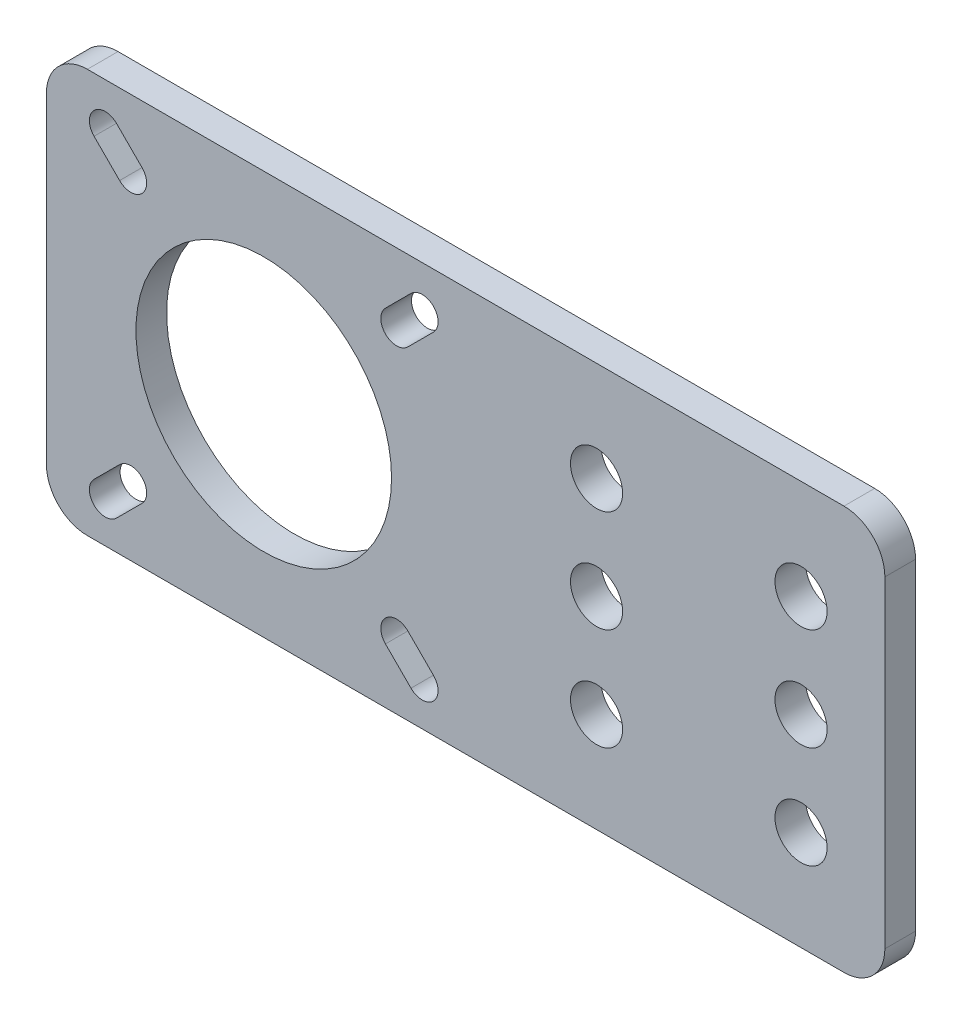
SolidWorks part; units mm, degrees
ref_plane "Alzado" through (0, 0, 0) normal (0, 0, 1) x (1, 0, 0)
ref_plane "Planta" through (0, 0, 0) normal (0, 1, 0) x (1, 0, 0)
ref_plane "Vista lateral" through (0, 0, 0) normal (1, 0, 0) x (0, 0, -1)
sketch "Croquis1" plane through (0, 0, 0) normal (0, 0, 1) x (1, 0, 0)
  line L1 (-36.0737, 51.8328) -> (37.9263, 51.8328)
  line L2 (-40.0737, 47.8328) -> (-40.0737, 16.3328)
  line L3 (-36.0737, 12.3328) -> (37.9263, 12.3328)
  line L4 (41.9263, 47.8328) -> (41.9263, 16.3328)
  line L11 (-4.4197, 15.2368) -> (-6.9197, 17.7368)
  line L12 (-35.4197, 17.4288) -> (-32.9197, 19.9288)
  line L13 (-33.2277, 15.2368) -> (-30.7277, 17.7368)
  line L14 (-2.2277, 17.4288) -> (-4.7277, 19.9288)
  line L15 (-2.2277, 46.4868) -> (-4.7277, 43.9868)
  line L16 (-4.4197, 48.6788) -> (-6.9197, 46.1788)
  line L17 (-33.2277, 48.6788) -> (-30.7277, 46.1788)
  line L18 (-35.4197, 46.4868) -> (-32.9197, 43.9868)
  arc A0 (41.9263, 47.8328) -> (37.9263, 51.8328) centre (37.9263, 47.8328) ccw
  arc A1 (37.9263, 12.3328) -> (41.9263, 16.3328) centre (37.9263, 16.3328) ccw
  arc A2 (-40.0737, 16.3328) -> (-36.0737, 12.3328) centre (-36.0737, 16.3328) ccw
  arc A3 (-40.0737, 47.8328) -> (-36.0737, 51.8328) centre (-36.0737, 47.8328) cw
  circle A4 centre (-18.8237, 32.0828) radius 12.5
  circle A5 centre (33.7263, 22.0828) radius 2.55
  circle A6 centre (33.7263, 32.0828) radius 2.55
  circle A7 centre (33.7263, 42.0828) radius 2.55
  circle A8 centre (13.7263, 22.0828) radius 2.55
  circle A9 centre (13.7263, 32.0828) radius 2.55
  circle A10 centre (13.7263, 42.0828) radius 2.55
  arc A11 (-35.4197, 17.4288) -> (-33.2277, 15.2368) centre (-34.3237, 16.3328) ccw
  arc A12 (-30.7277, 17.7368) -> (-32.9197, 19.9288) centre (-31.8237, 18.8328) ccw
  arc A13 (-6.9197, 17.7368) -> (-4.7277, 19.9288) centre (-5.8237, 18.8328) cw
  arc A14 (-2.2277, 17.4288) -> (-4.4197, 15.2368) centre (-3.3237, 16.3328) cw
  arc A15 (-2.2277, 46.4868) -> (-4.4197, 48.6788) centre (-3.3237, 47.5828) ccw
  arc A16 (-6.9197, 46.1788) -> (-4.7277, 43.9868) centre (-5.8237, 45.0828) ccw
  arc A17 (-30.7277, 46.1788) -> (-32.9197, 43.9868) centre (-31.8237, 45.0828) cw
  arc A18 (-35.4197, 46.4868) -> (-33.2277, 48.6788) centre (-34.3237, 47.5828) cw
  dimension "D1" = 4
  dimension "D2" = 9.75
  dimension "D4" = 53.8
  dimension "D3" = 73.8
  dimension "D5" = 36.75
  dimension "D6" = 34.25
  dimension "D7" = 21.25
  dimension "D8" = 8.25
  dimension "D9" = 5.75
  dimension "D10" = 19.75
  dimension "D11" = 32.75
  dimension "D12" = 35.25
  dimension "D13" = 39.5
  dimension "D14" = 82
  dimension "D15" = 9.75
  dimension "D16" = 10
  dimension "D17" = 10
  dimension "D18" = 20
  dimension "D19" = 8.2
extrude "Saliente-Extruir1" add sketch "Croquis1" along normal blind 3
